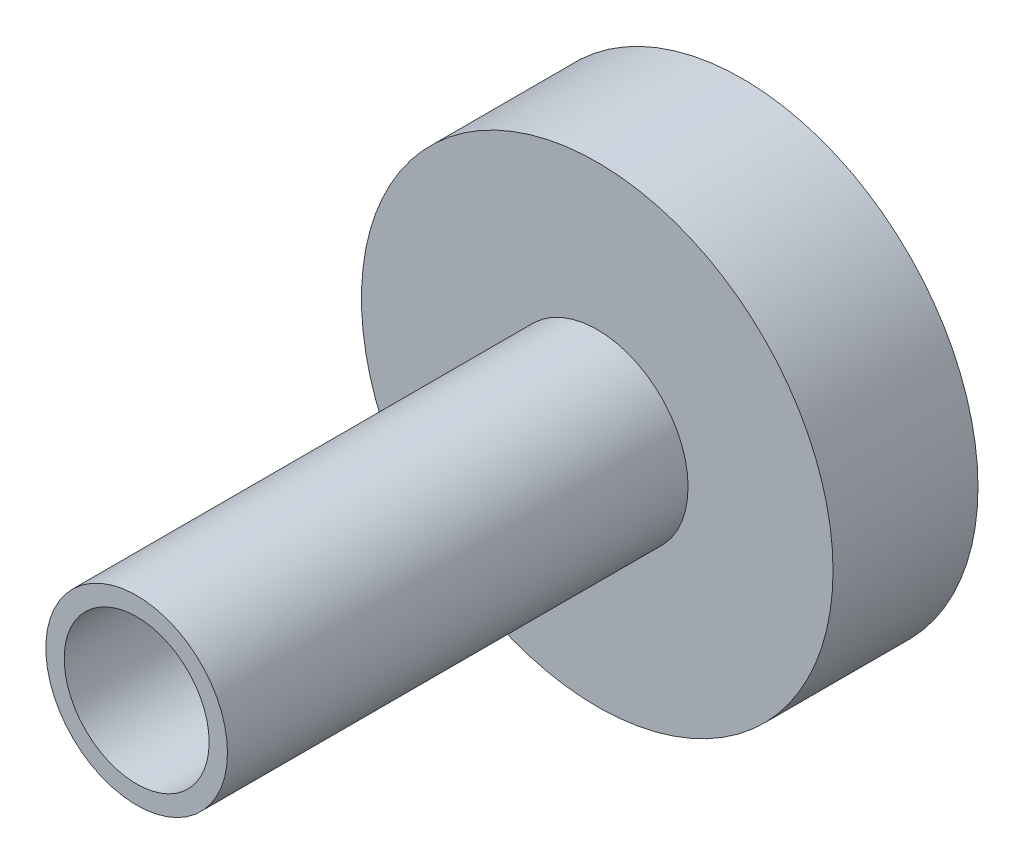
SolidWorks part; units mm, degrees
ref_plane "Front Plane" through (0, 0, 0) normal (0, 0, 1) x (1, 0, 0)
ref_plane "Top Plane" through (0, 0, 0) normal (0, 1, 0) x (1, 0, 0)
ref_plane "Right Plane" through (0, 0, 0) normal (1, 0, 0) x (0, 0, -1)
sketch "Sketch1" plane through (0, 0, 0) normal (0, 0, 1) x (1, 0, 0)
  circle A0 centre (0, 0) radius 12.85
  circle A1 centre (0, 0) radius 3.95
  dimension "D1" = 25.7
  dimension "D2" = 7.9
extrude "Boss-Extrude1" add sketch "Sketch1" along normal blind 33
sketch "Sketch2" plane through (0, 0, 33) normal (0, 0, 1) x (1, 0, 0)
  circle A0 centre (0, 0) radius 4.95
  circle A1 centre (0, 0) radius 12.85
  circle A2 centre (0, 0) radius 12.85 construction
  dimension "D1" = 9.9
extrude "Cut-Extrude1" cut sketch "Sketch2" against normal blind 25.1
